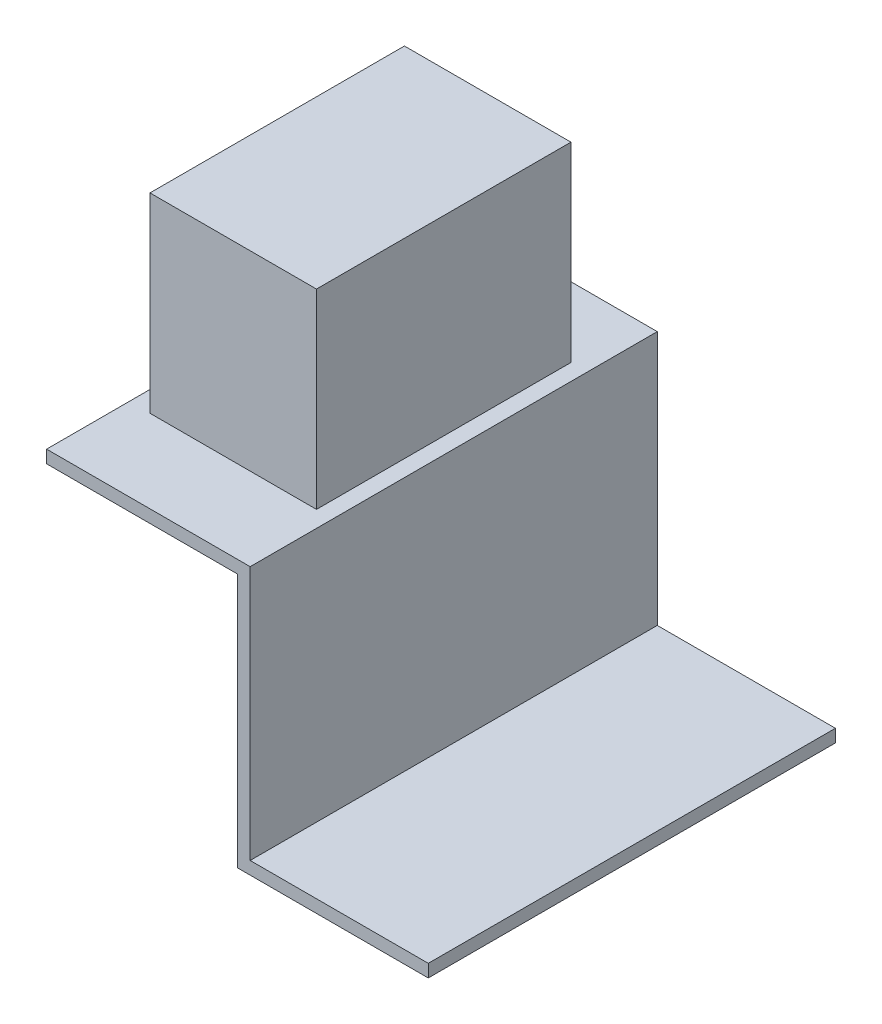
SolidWorks part; units mm, degrees
ref_plane "前视基准面" through (0, 0, 0) normal (0, 0, 1) x (1, 0, 0)
ref_plane "上视基准面" through (0, 0, 0) normal (0, 1, 0) x (1, 0, 0)
ref_plane "右视基准面" through (0, 0, 0) normal (1, 0, 0) x (0, 0, -1)
sketch "草图1" plane through (0, 0, 0) normal (0, 1, 0) x (1, 0, 0)
  line L1 (-7.5, 16) -> (7.5, 16)
  line L2 (-7.5, 16) -> (-7.5, -16)
  line L3 (-7.5, -16) -> (7.5, -16)
  line L4 (7.5, 16) -> (7.5, -16)
  line L5 (-7.5, 16) -> (7.5, -16) construction
  line L6 (-7.5, -16) -> (7.5, 16) construction
  point P0 (0, 0)
  dimension "D1" = 32
  dimension "D2" = 15
extrude "凸台-拉伸1" add sketch "草图1" along normal blind 1
sketch "草图2" plane through (0, 1, 0) normal (0, 1, 0) x (1, 0, 0)
  line L0 (-7.5, -16) -> (7.5, -16) construction
  line L1 (-7.5, 16) -> (-6.5, 16)
  line L2 (-7.5, 16) -> (-7.5, -16)
  line L3 (-7.5, -16) -> (-6.5, -16)
  line L4 (-6.5, 16) -> (-6.5, -16)
  dimension "D1" = 1
extrude "凸台-拉伸2" add sketch "草图2" along normal blind 20
sketch "草图8" plane through (-7.5, 0, 0) normal (-1, 0, 0) x (0, 0, 1)
  line L0 (16, 21) -> (16, 0) construction
  line L1 (-16, 21) -> (16, 21)
  line L2 (-16, 21) -> (-16, 20)
  line L3 (-16, 20) -> (16, 20)
  line L4 (16, 21) -> (16, 20)
  dimension "D1" = 1
extrude "凸台-拉伸8" add sketch "草图8" along normal blind 15
sketch "草图9" plane through (0, 21, 0) normal (0, 1, 0) x (1, 0, 0)
  line L1 (-20.8783, 10.5037) -> (-7.791, 10.5037)
  line L2 (-20.8783, 10.5037) -> (-20.8783, -9.4963)
  line L3 (-20.8783, -9.4963) -> (-7.791, -9.4963)
  line L4 (-7.791, 10.5037) -> (-7.791, -9.4963)
  line L5 (-20.8783, 10.5037) -> (-7.791, -9.4963) construction
  line L6 (-20.8783, -9.4963) -> (-7.791, 10.5037) construction
  point P0 (-14.3347, 0.5037)
  dimension "D1" = 20
extrude "凸台-拉伸9" add sketch "草图9" along normal blind 15
sketch "草图10" plane through (-20.8783, 0, 0) normal (-1, 0, 0) x (0, 0, 1)
  circle A0 centre (0, 28.5) radius 2.7968
extrude "凸台-拉伸10" add sketch "草图10" along normal blind 3
